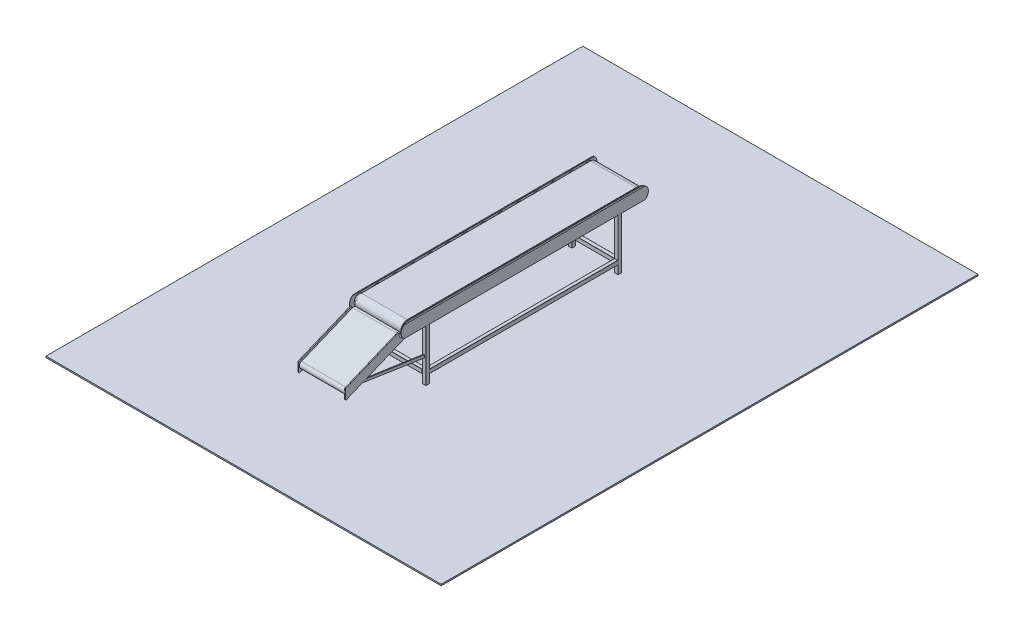
SolidWorks part; units mm, degrees
ref_plane "Front Plane" through (0, 0, 0) normal (0, 0, 1) x (1, 0, 0)
ref_plane "Top Plane" through (0, 0, 0) normal (0, 1, 0) x (1, 0, 0)
ref_plane "Right Plane" through (0, 0, 0) normal (1, 0, 0) x (0, 0, -1)
sketch "Sketch1" plane through (0, 0, 0) normal (1, 0, 0) x (0, 0, -1)
  line L0 (-1250, 0) -> (1250, 0) construction
  line L1 (-1250, 60) -> (1250, 60)
  line L2 (-1250, -60) -> (1250, -60)
  arc A0 (-1250, 60) -> (-1250, -60) centre (-1250, 0) ccw
  arc A1 (1250, -60) -> (1250, 60) centre (1250, 0) ccw
  point P2 (0, 0)
  dimension "D2" = 60
  dimension "D1" = 2500
extrude "Extrude-Thin1" add sketch "Sketch1" along normal mid plane 500 thin thin type one direction wall 10
sketch "Sketch2" plane through (0, 0, 0) normal (1, 0, 0) x (0, 0, -1)
  circle A0 centre (-1250, 0) radius 60
extrude "Boss-Extrude1" add sketch "Sketch2" along normal mid plane 550 separate body
chamfer "Chamfer1" distance 5 angle 45 2 edges at (-275, 0, 1190) (275, 0, 1190)
pattern_linear "LPattern1" count 14 spacing 192 along (0, 0, -1) of bodies 102
sketch "Sketch4" plane through (0, 0, 0) normal (0, 0, 1) x (1, 0, 0)
  line L0 (-265.9025, 76.891) -> (-272.6823, 76.891)
  line L1 (-279.7345, 66.891) -> (-279.7345, -59.5919)
  line L2 (-269.7345, -69.5919) -> (-265.9025, -69.5919)
  line L3 (-265.9025, 78.891) -> (-274.6823, 78.891)
  line L4 (-281.7345, 68.891) -> (-281.7345, -61.5919)
  line L5 (-271.7345, -71.5919) -> (-265.9025, -71.5919)
  line L6 (-265.9025, -71.5919) -> (-265.9025, -69.5919)
  line L7 (-265.9025, 78.891) -> (-265.9025, 76.891)
  line L8 (-265.9025, 78.891) -> (-281.7345, 78.891) construction
  line L9 (-281.7345, 78.891) -> (-281.7345, -71.5919) construction
  line L10 (-274.6823, 78.891) -> (-281.7345, 68.891)
  line L11 (-265.9025, 76.891) -> (-279.7345, 76.891) construction
  line L12 (-279.7345, 76.891) -> (-279.7345, -69.5919) construction
  line L13 (-272.6823, 76.891) -> (-279.7345, 66.891)
  line L14 (-279.7345, -69.5919) -> (-265.9025, -69.5919) construction
  line L15 (-279.7345, -59.5919) -> (-269.7345, -69.5919)
  line L16 (-281.7345, -71.5919) -> (-265.9025, -71.5919) construction
  line L17 (-281.7345, -61.5919) -> (-271.7345, -71.5919)
  line L18 (0, 0) -> (0, 162.7407) construction
  line L21 (281.7345, -61.5919) -> (271.7345, -71.5919)
  line L22 (279.7345, -59.5919) -> (269.7345, -69.5919)
  line L23 (272.6823, 76.891) -> (279.7345, 66.891)
  line L24 (274.6823, 78.891) -> (281.7345, 68.891)
  line L25 (265.9025, 78.891) -> (265.9025, 76.891)
  line L26 (265.9025, -71.5919) -> (265.9025, -69.5919)
  line L27 (271.7345, -71.5919) -> (265.9025, -71.5919)
  line L28 (281.7345, 68.891) -> (281.7345, -61.5919)
  line L29 (265.9025, 78.891) -> (274.6823, 78.891)
  line L30 (269.7345, -69.5919) -> (265.9025, -69.5919)
  line L31 (279.7345, 66.891) -> (279.7345, -59.5919)
  line L32 (265.9025, 76.891) -> (272.6823, 76.891)
  dimension "D1" = 2
extrude "Boss-Extrude2" add sketch "Sketch4" along normal mid plane 2700 separate body
sketch "Sketch8" plane through (281.7345, 0, 0) normal (1, 0, 0) x (0, 0, -1)
  line L0 (-1274.7586, 3.6495) -> (1274.9874, 3.6495) construction
  line L1 (-1274.7586, 78.891) -> (1274.9874, 78.891)
  line L2 (-1274.7586, -71.5919) -> (1274.9874, -71.5919)
  line L4 (-1350, -71.5919) -> (1350, -71.5919) construction
  line L5 (-1350, 78.891) -> (1350, 78.891) construction
  line L6 (-1350, -61.5919) -> (-1350, 68.891) construction
  line L8 (-1420.5128, -130.4732) -> (1420.7417, -130.4732)
  line L9 (-1420.5128, -130.4732) -> (-1420.5128, 137.7722)
  line L10 (-1420.5128, 137.7722) -> (1420.7417, 137.7722)
  line L11 (1420.7417, -130.4732) -> (1420.7417, 137.7722)
  line L12 (-1420.5128, -130.4732) -> (1420.7417, 137.7722) construction
  line L13 (-1420.5128, 137.7722) -> (1420.7417, -130.4732) construction
  arc A0 (-1274.7586, 78.891) -> (-1274.7586, -71.5919) centre (-1274.7586, 3.6495) ccw
  arc A1 (1274.9874, -71.5919) -> (1274.9874, 78.891) centre (1274.9874, 3.6495) ccw
  point P2 (0.1144, 3.6495)
  point P8 (0.1144, 3.6495)
extrude "Cut-Extrude1" cut sketch "Sketch8" against normal blind 570
sketch "Sketch5" plane through (0, -71.5919, 0) normal (0, -1, 0) x (1, 0, 0)
  line L1 (-233.7345, -1068.9818) -> (-269.7345, -1068.9818)
  line L2 (-231.7345, -1066.9818) -> (-231.7345, -1030.9818)
  line L3 (-233.7345, -1028.9818) -> (-269.7345, -1028.9818)
  line L4 (-271.7345, -1066.9818) -> (-271.7345, -1030.9818)
  line L5 (-231.7345, -1068.9818) -> (-271.7345, -1028.9818) construction
  line L6 (-231.7345, -1028.9818) -> (-271.7345, -1068.9818) construction
  line L7 (-271.7345, 1274.7586) -> (-271.7345, -1274.9874) construction
  line L8 (0, -1250) -> (0, -951.8224) construction
  line L9 (250, -1250) -> (-250, -1250) construction
  line L10 (231.7345, -1028.9818) -> (271.7345, -1068.9818) construction
  line L11 (231.7345, -1068.9818) -> (271.7345, -1028.9818) construction
  line L12 (271.7345, -1066.9818) -> (271.7345, -1030.9818)
  line L13 (233.7345, -1028.9818) -> (269.7345, -1028.9818)
  line L14 (231.7345, -1066.9818) -> (231.7345, -1030.9818)
  line L15 (233.7345, -1068.9818) -> (269.7345, -1068.9818)
  arc A0 (-269.7345, -1068.9818) -> (-271.7345, -1066.9818) centre (-269.7345, -1066.9818) cw
  arc A1 (-231.7345, -1030.9818) -> (-233.7345, -1028.9818) centre (-233.7345, -1030.9818) ccw
  arc A2 (-233.7345, -1068.9818) -> (-231.7345, -1066.9818) centre (-233.7345, -1066.9818) ccw
  arc A3 (-269.7345, -1028.9818) -> (-271.7345, -1030.9818) centre (-269.7345, -1030.9818) ccw
  arc A4 (269.7345, -1028.9818) -> (271.7345, -1030.9818) centre (269.7345, -1030.9818) cw
  arc A5 (233.7345, -1068.9818) -> (231.7345, -1066.9818) centre (233.7345, -1066.9818) cw
  arc A6 (231.7345, -1030.9818) -> (233.7345, -1028.9818) centre (233.7345, -1030.9818) cw
  arc A7 (269.7345, -1068.9818) -> (271.7345, -1066.9818) centre (269.7345, -1066.9818) ccw
  point P0 (-251.7345, -1048.9818)
  point P40 (251.7345, -1048.9818)
  dimension "D3" = 2
  dimension "D1" = 40
  dimension "D2" = 40
extrude "Boss-Extrude3" add sketch "Sketch5" along normal blind 570 separate body
mirror "Mirror1" about plane through (0, 0, 0) normal (0, 0, 1) of bodies 118 119
sketch "Sketch6" plane through (0, 0, 1028.9818) normal (0, 0, -1) x (-1, 0, 0)
  line L0 (233.7345, -641.5919) -> (233.7345, -71.5919) construction
  line L1 (235.7345, -499.4718) -> (267.7345, -499.4718)
  line L2 (233.7345, -501.4718) -> (233.7345, -540.8903)
  line L3 (235.7345, -542.8903) -> (267.7345, -542.8903)
  line L4 (269.7345, -501.4718) -> (269.7345, -540.8903)
  line L5 (269.7345, -641.5919) -> (269.7345, -71.5919) construction
  line L6 (0, -492.7302) -> (0, -389.198) construction
  line L7 (-269.7345, -501.4718) -> (-269.7345, -540.8903)
  line L8 (-235.7345, -542.8903) -> (-267.7345, -542.8903)
  line L9 (-233.7345, -501.4718) -> (-233.7345, -540.8903)
  line L10 (-235.7345, -499.4718) -> (-267.7345, -499.4718)
  arc A0 (267.7345, -499.4718) -> (269.7345, -501.4718) centre (267.7345, -501.4718) cw
  arc A1 (233.7345, -540.8903) -> (235.7345, -542.8903) centre (235.7345, -540.8903) ccw
  arc A2 (267.7345, -542.8903) -> (269.7345, -540.8903) centre (267.7345, -540.8903) ccw
  arc A3 (235.7345, -499.4718) -> (233.7345, -501.4718) centre (235.7345, -501.4718) ccw
  arc A4 (-235.7345, -499.4718) -> (-233.7345, -501.4718) centre (-235.7345, -501.4718) cw
  arc A5 (-267.7345, -542.8903) -> (-269.7345, -540.8903) centre (-267.7345, -540.8903) cw
  arc A6 (-233.7345, -540.8903) -> (-235.7345, -542.8903) centre (-235.7345, -540.8903) cw
  arc A7 (-267.7345, -499.4718) -> (-269.7345, -501.4718) centre (-267.7345, -501.4718) ccw
  point P14 (269.7345, -542.8903)
  point P17 (233.7345, -499.4718)
  dimension "D1" = 2
extrude "Boss-Extrude4" add sketch "Sketch6" along normal up to surface (2057.9637 mm away) up to face at (-251.7345, -356.5919, -1028.9818)
sketch "Sketch7" plane through (231.7345, 0, 0) normal (-1, 0, 0) x (0, 0, 1)
  line L0 (-1068.9818, -641.5919) -> (-1068.9818, -71.5919) construction
  line L1 (-1030.9818, -499.4718) -> (-1066.9818, -499.4718)
  line L2 (-1028.9818, -501.4718) -> (-1028.9818, -540.7686)
  line L3 (-1030.9818, -542.7686) -> (-1066.9818, -542.7686)
  line L4 (-1068.9818, -501.4718) -> (-1068.9818, -540.7686)
  line L5 (0, 0) -> (0, -833.3145) construction
  line L6 (1068.9818, -501.4718) -> (1068.9818, -540.7686)
  line L7 (1030.9818, -542.7686) -> (1066.9818, -542.7686)
  line L8 (1028.9818, -501.4718) -> (1028.9818, -540.7686)
  line L9 (1030.9818, -499.4718) -> (1066.9818, -499.4718)
  arc A0 (-1066.9818, -499.4718) -> (-1068.9818, -501.4718) centre (-1066.9818, -501.4718) ccw
  arc A1 (-1028.9818, -540.7686) -> (-1030.9818, -542.7686) centre (-1030.9818, -540.7686) cw
  arc A2 (-1066.9818, -542.7686) -> (-1068.9818, -540.7686) centre (-1066.9818, -540.7686) cw
  arc A3 (-1030.9818, -499.4718) -> (-1028.9818, -501.4718) centre (-1030.9818, -501.4718) cw
  arc A4 (1030.9818, -499.4718) -> (1028.9818, -501.4718) centre (1030.9818, -501.4718) ccw
  arc A5 (1066.9818, -542.7686) -> (1068.9818, -540.7686) centre (1066.9818, -540.7686) ccw
  arc A6 (1028.9818, -540.7686) -> (1030.9818, -542.7686) centre (1030.9818, -540.7686) ccw
  arc A7 (1066.9818, -499.4718) -> (1068.9818, -501.4718) centre (1066.9818, -501.4718) cw
  point P13 (-1068.9818, -542.7686)
  point P16 (-1028.9818, -499.4718)
  dimension "D1" = 2
extrude "Boss-Extrude5" add sketch "Sketch7" along normal up to surface (463.469 mm away) up to face at (-231.7345, -356.5919, 1048.9818)
sketch "Sketch9" plane through (0, 0, 0) normal (1, 0, 0) x (0, 0, -1)
  line L0 (-1334.921, -51.9466) -> (-1892.5273, -281.0288) construction
  line L1 (-1324.7549, -76.6917) -> (-1882.3612, -305.774)
  line L2 (-1345.0871, -27.2014) -> (-1902.6933, -256.2837)
  arc A0 (-1324.7549, -76.6917) -> (-1345.0871, -27.2014) centre (-1334.921, -51.9466) ccw
  arc A1 (-1902.6933, -256.2837) -> (-1882.3612, -305.774) centre (-1892.5273, -281.0288) ccw
  point P2 (-1613.7241, -166.4877)
  point P7 (-1913.0407, -289.8203)
  point P8 (-1320.6371, -123.1668)
  point P9 (-1365.6005, -35.9929)
extrude "Extrude-Thin2" add sketch "Sketch9" along normal mid plane 500 separate body thin thin type one direction wall 10
sketch "Sketch10" plane through (250, 0, 0) normal (1, 0, 0) x (0, 0, -1)
  line L0 (-1358.2271, 2.4632) -> (-1930.1612, -234.4006)
  line L1 (-1936.3349, -243.6396) -> (-1936.3349, -334.4504)
  line L2 (-1922.5086, -343.6895) -> (-1274.8362, -75.4591)
  arc A0 (-1358.2271, 2.4632) -> (-1274.8362, -75.4591) centre (-1275.8158, 7.0754) ccw
  arc A1 (-1936.3349, -334.4504) -> (-1922.5086, -343.6895) centre (-1926.3349, -334.4504) ccw
  arc A2 (-1930.1612, -234.4006) -> (-1936.3349, -243.6396) centre (-1926.3349, -243.6396) ccw
  point P5 (-1274.8366, -75.4591)
  point P6 (-1287.222, -77.7349)
  point P7 (-1285.5151, -77.7349)
  point P8 (-1351.8002, -2.3462)
  dimension "D1" = 10
extrude "Boss-Extrude6" add sketch "Sketch10" along normal blind 10 separate body
mirror "Mirror3" about plane through (0, 0, 0) normal (1, 0, 0) of bodies 130
sketch "Sketch11" plane through (0, 386.2586, 159.9671) normal (0, -0.9239, -0.3826) x (1, 0, 0)
  line L0 (250, 1907.715) -> (250, 1206.6964) construction
  line L1 (250, 1721.7877) -> (260, 1721.7877)
  line L2 (250, 1721.7877) -> (250, 1671.6038)
  line L3 (250, 1671.6038) -> (260, 1671.6038)
  line L4 (260, 1721.7877) -> (260, 1671.6038)
  line L5 (260, 1907.715) -> (260, 1206.6964) construction
sketch "Sketch12" plane through (0, 0, 1068.9818) normal (0, 0, 1) x (1, 0, 0)
  line L1 (250.3925, -346.1462) -> (258.9602, -346.1462)
  line L2 (250.3925, -346.1462) -> (250.3925, -377.437)
  line L3 (250.3925, -377.437) -> (258.9602, -377.437)
  line L4 (258.9602, -346.1462) -> (258.9602, -377.437)
loft "Loft1" add profiles "Sketch12", "Sketch11"
mirror "Mirror4" about plane through (0, 0, 0) normal (1, 0, 0) of bodies 133
sketch "Sketch13" plane through (0, -641.5919, 0) normal (0, -1, 0) x (1, 0, 0)
  line L1 (-2081.8823, 2863.5361) -> (2233.0805, 2863.5361)
  line L2 (-2081.8823, 2863.5361) -> (-2081.8823, -2998.3001)
  line L3 (-2081.8823, -2998.3001) -> (2233.0805, -2998.3001)
  line L4 (2233.0805, 2863.5361) -> (2233.0805, -2998.3001)
extrude "Boss-Extrude8" add sketch "Sketch13" along normal mid plane 15 separate body
